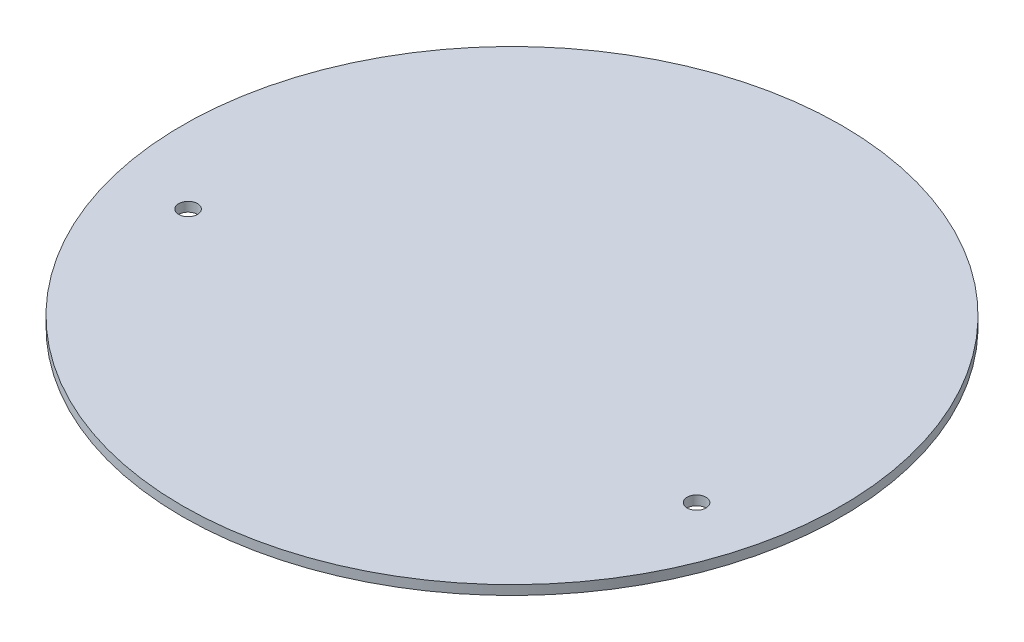
SolidWorks part; units mm, degrees
ref_plane "Front Plane" through (0, 0, 0) normal (0, 0, 1) x (1, 0, 0)
ref_plane "Top Plane" through (0, 0, 0) normal (0, 1, 0) x (1, 0, 0)
ref_plane "Right Plane" through (0, 0, 0) normal (1, 0, 0) x (0, 0, -1)
sketch "Sketch1" plane through (0, 0, 0) normal (0, 1, 0) x (1, 0, 0)
  line L0 (-27, -7.4) -> (27, -7.4) construction
  circle A0 centre (0, 0) radius 35
  circle A1 centre (-27, -7.4) radius 1
  circle A2 centre (27, -7.4) radius 1
  point P7 (0, -7.4)
  point P8 (0, 0)
  dimension "D1" = 70
  dimension "D2" = 2
  dimension "D3" = 7.4
  dimension "D4" = 54
extrude "Boss-Extrude1" add sketch "Sketch1" along normal mid plane 1
